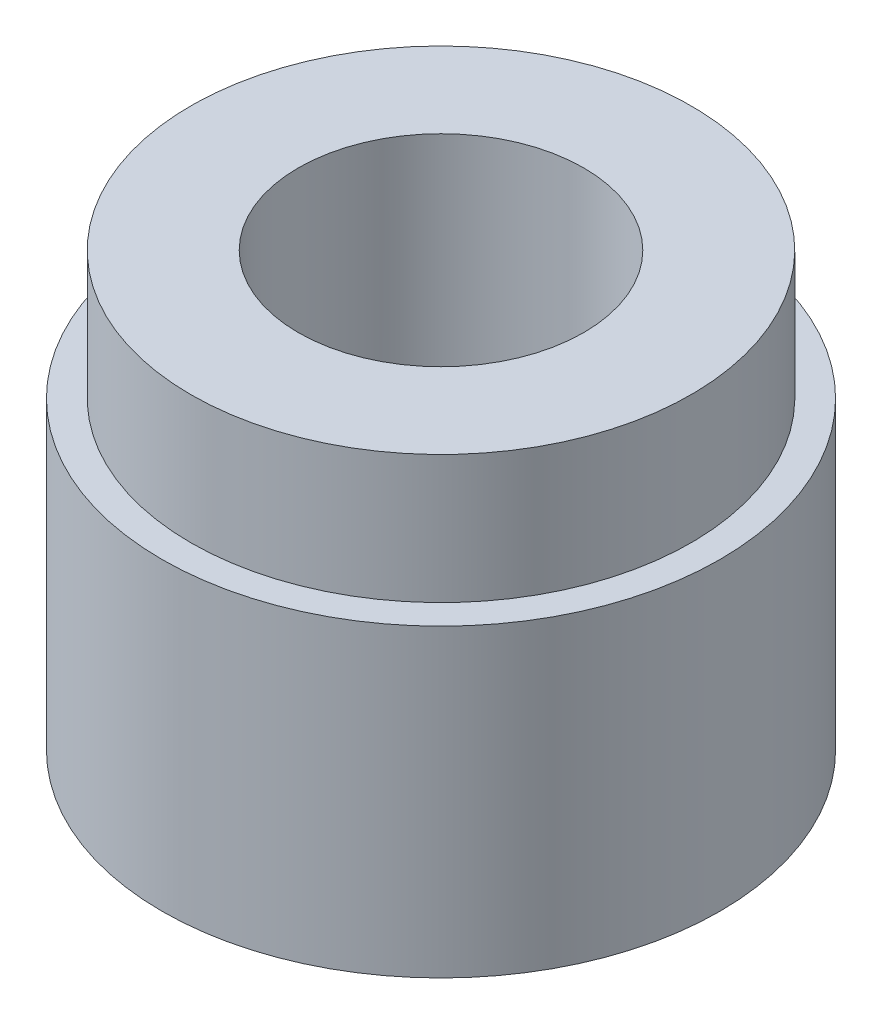
SolidWorks part; units mm, degrees
ref_plane "Front Plane" through (0, 0, 0) normal (0, 0, 1) x (1, 0, 0)
ref_plane "Top Plane" through (0, 0, 0) normal (0, 1, 0) x (1, 0, 0)
ref_plane "Right Plane" through (0, 0, 0) normal (1, 0, 0) x (0, 0, -1)
sketch "Sketch1" plane through (0, 0, 0) normal (0, 1, 0) x (1, 0, 0)
  circle A0 centre (0, 0) radius 2.2098
  dimension "D1" = 4.4196
extrude "Boss-Extrude1" add sketch "Sketch1" along normal blind 3.429
sketch "Sketch2" plane through (0, 3.429, 0) normal (0, 1, 0) x (1, 0, 0)
  circle A0 centre (0, 0) radius 1.9812
  dimension "D1" = 3.9624
extrude "Cut-Extrude1" cut sketch "Sketch2" against normal blind 1.016 flip side to cut
hole_wizard "#4-40 Tapped Hole1" positions "Sketch5" profile "Sketch4" tap size "#4-40" standard "ANSI Inch"
sketch "Sketch5" plane through (0, 0, 0) normal (0, -1, 0) x (-1, 0, 0)
  point P0 (0, 0)
sketch "Sketch4" plane through (0, 0, 0) normal (1, 0, 0) x (0, 0, -1)
  line L0 (0, 0) -> (0, 9.5438)
  line L1 (0, 9.5438) -> (1.1303, 8.8646)
  line L2 (1.1303, 8.8646) -> (1.1303, 0)
  line L5 (1.1303, 0) -> (0, 0)
  line L10 (0, 9.5438) -> (-1.1303, 8.8646) construction
  line L11 (0, -6.35) -> (0, 107.95) construction
  dimension "Tap Drill Dia." = 2.2606
  dimension "Tap Drill Depth" = 8.8646
  dimension "Drill Angle" = 118
cosmetic thread "Hole Thread1" parameters "D1"=3.429, "D2"=2.8448
